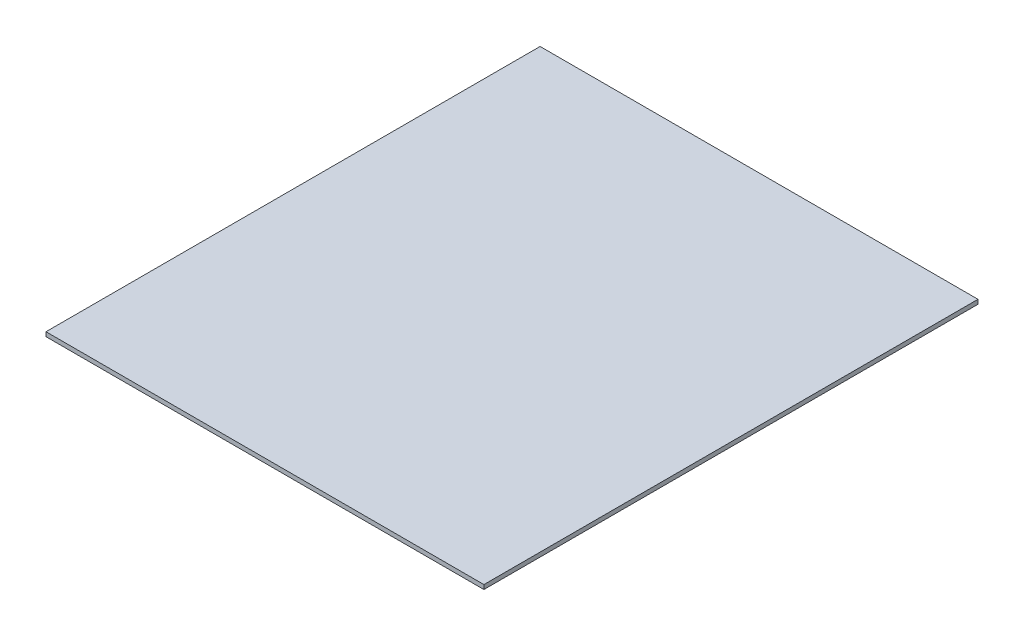
SolidWorks part; units mm, degrees
ref_plane "Front Plane" through (0, 0, 0) normal (0, 0, 1) x (1, 0, 0)
ref_plane "Top Plane" through (0, 0, 0) normal (0, 1, 0) x (1, 0, 0)
ref_plane "Right Plane" through (0, 0, 0) normal (1, 0, 0) x (0, 0, -1)
sketch "Sketch1" plane through (0, 0, 0) normal (0, 1, 0) x (1, 0, 0)
  line L1 (-1325.5413, 43.9091) -> (-1629.5413, 43.9091)
  line L2 (-1325.5413, 43.9091) -> (-1325.5413, 386.9091)
  line L3 (-1325.5413, 386.9091) -> (-1629.5413, 386.9091)
  line L4 (-1629.5413, 43.9091) -> (-1629.5413, 386.9091)
  dimension "D1" = 304
  dimension "D2" = 343
extrude "Boss-Extrude1" add sketch "Sketch1" along normal blind 3
